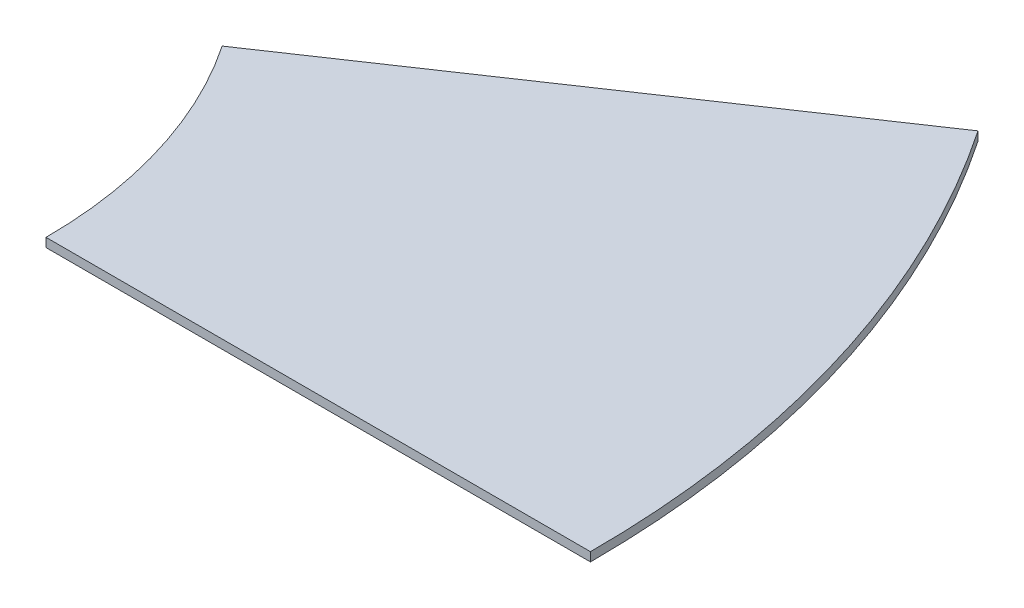
SolidWorks part; units mm, degrees
ref_plane "Front" through (0, 0, 0) normal (0, 0, 1) x (1, 0, 0)
ref_plane "Top" through (0, 0, 0) normal (0, 1, 0) x (1, 0, 0)
ref_plane "Right" through (0, 0, 0) normal (1, 0, 0) x (0, 0, -1)
sketch "草图1" plane through (0, 0, 0) normal (0, 1, 0) x (1, 0, 0)
  line L0 (0, 0) -> (110, 0) construction
  line L1 (91.1941, 61.5112) -> (0, 0) construction
  line L2 (91.1941, 61.5112) -> (41.4519, 27.9596)
  line L3 (110, 0) -> (50, 0)
  arc A0 (110, 0) -> (91.1941, 61.5112) centre (0, 0) ccw
  arc A1 (50, 0) -> (41.4519, 27.9596) centre (0, 0) ccw
  dimension "D2" = 50
  dimension "D3" = 110
  dimension "D1" = 34
extrude "凸台-拉伸1" add sketch "草图1" along normal blind 0.98 contours L3 A1 L2 A0
